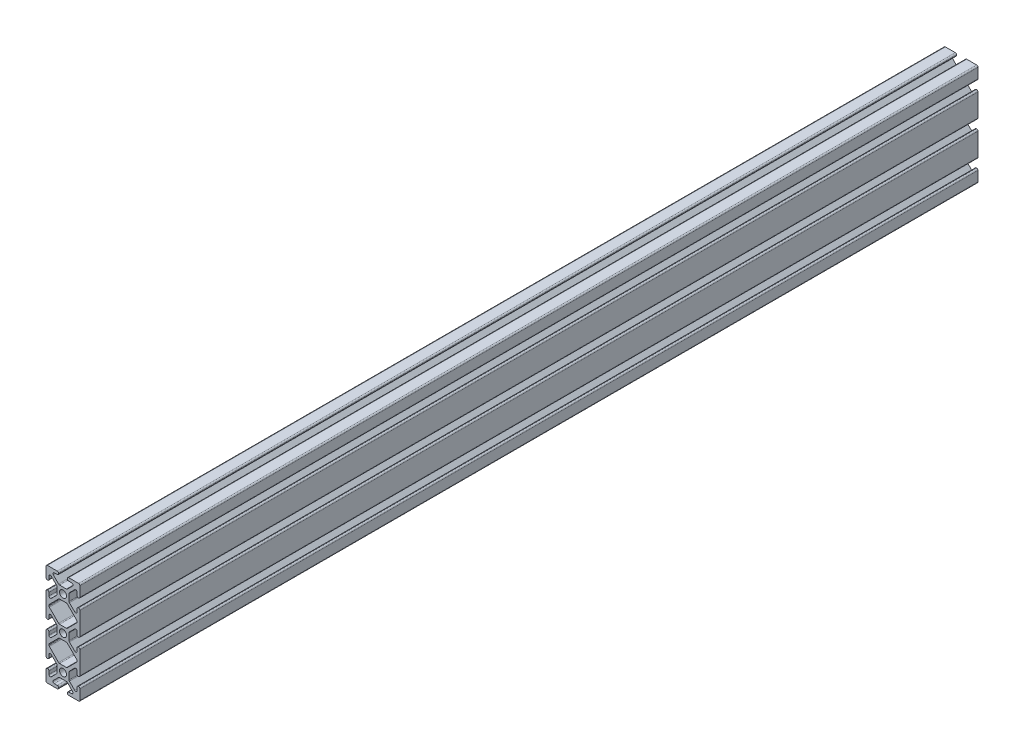
SolidWorks part; units mm, degrees
ref_plane "Front Plane" through (0, 0, 0) normal (0, 0, 1) x (1, 0, 0)
ref_plane "Top Plane" through (0, 0, 0) normal (0, 1, 0) x (1, 0, 0)
ref_plane "Right Plane" through (0, 0, 0) normal (1, 0, 0) x (0, 0, -1)
sketch "Sketch1" plane through (0, 0, 0) normal (0, 0, 1) x (1, 0, 0)
  line L0 (-12.7, 38.1) -> (-12.7, 12.7) construction
  line L1 (-12.7, -38.1) -> (12.7, -38.1) construction
  line L2 (-12.7, 12.7) -> (-12.7, -12.7) construction
  line L3 (-12.7, 38.1) -> (12.7, 38.1) construction
  line L4 (-12.7, -12.7) -> (-12.7, -38.1) construction
  line L5 (-12.7, -38.1) -> (12.7, 38.1) construction
  line L6 (-12.7, 38.1) -> (12.7, -38.1) construction
  line L7 (12.7, 38.1) -> (12.7, 12.7) construction
  line L8 (12.7, 12.7) -> (12.7, -12.7) construction
  line L9 (12.7, -12.7) -> (12.7, -38.1) construction
  line L10 (-12.7, 12.7) -> (12.7, 12.7) construction
  line L11 (-12.7, -12.7) -> (12.7, -12.7) construction
  line L12 (12.7, -12.7) -> (-12.7, -38.1) construction
  line L13 (12.7, -38.1) -> (-12.7, -12.7) construction
  line L14 (0, 38.1) -> (0, -38.1) construction
  line L15 (12.7, 12.7) -> (-12.7, 38.1) construction
  line L16 (12.7, 38.1) -> (-12.7, 12.7) construction
  line L17 (-12.7, 37.084) -> (-12.7, 29.6672)
  line L18 (-11.684, 28.6512) -> (-11.5062, 28.6512)
  line L19 (-10.4902, 29.6672) -> (-10.4902, 31.8748)
  line L20 (-8.7558, 32.5932) -> (-4.8188, 28.6562)
  line L21 (-4.5212, 27.9378) -> (-4.5212, 22.8622)
  line L22 (-4.8188, 22.1438) -> (-8.7558, 18.2068)
  line L23 (-10.4902, 18.9252) -> (-10.4902, 21.1328)
  line L24 (-11.5062, 22.1488) -> (-11.684, 22.1488)
  line L25 (-12.7, 21.1328) -> (-12.7, 4.2672)
  line L26 (-12.7, 0) -> (12.7, 0) construction
  line L27 (-12.7, -25.4) -> (12.7, -25.4) construction
  line L28 (-12.7, 25.4) -> (12.7, 25.4) construction
  line L29 (4.2672, 38.1) -> (11.684, 38.1)
  line L30 (3.2512, 36.9062) -> (3.2512, 37.084)
  line L31 (6.4748, 35.8902) -> (4.2672, 35.8902)
  line L32 (3.2562, 30.2188) -> (7.1932, 34.1558)
  line L33 (-2.5378, 29.9212) -> (2.5378, 29.9212)
  line L34 (-7.1932, 34.1558) -> (-3.2562, 30.2188)
  line L35 (-4.2672, 35.8902) -> (-6.4748, 35.8902)
  line L36 (-3.2512, 37.084) -> (-3.2512, 36.9062)
  line L37 (-11.684, 38.1) -> (-4.2672, 38.1)
  line L38 (4.5212, 2.5378) -> (4.5212, -2.5378)
  line L39 (11.5062, 22.1488) -> (11.684, 22.1488)
  line L40 (10.4902, 18.9252) -> (10.4902, 21.1328)
  line L41 (4.8188, 22.1438) -> (8.7558, 18.2068)
  line L42 (4.5212, 27.9378) -> (4.5212, 22.8622)
  line L43 (8.7558, 32.5932) -> (4.8188, 28.6562)
  line L44 (10.4902, 29.6672) -> (10.4902, 31.8748)
  line L45 (11.684, 28.6512) -> (11.5062, 28.6512)
  line L46 (12.7, 37.084) -> (12.7, 29.6672)
  line L47 (-10.4902, 12.4736) -> (-10.4902, 12.9264)
  line L48 (-10.1926, 13.6448) -> (-3.2562, 20.5812)
  line L49 (-2.5378, 20.8788) -> (2.5378, 20.8788)
  line L50 (10.4902, 12.4736) -> (10.4902, 12.9264)
  line L51 (10.1926, 13.6448) -> (3.2562, 20.5812)
  line L52 (10.1926, 11.7552) -> (3.2562, 4.8188)
  line L53 (-2.5378, 4.5212) -> (2.5378, 4.5212)
  line L54 (-10.1926, 11.7552) -> (-3.2562, 4.8188)
  line L55 (-2.5378, -4.5212) -> (2.5378, -4.5212)
  line L56 (-10.1926, -11.7552) -> (-3.2562, -4.8188)
  line L57 (10.1926, -11.7552) -> (3.2562, -4.8188)
  line L58 (10.4902, -12.4736) -> (10.4902, -12.9264)
  line L59 (10.1926, -13.6448) -> (3.2562, -20.5812)
  line L60 (-2.5378, -20.8788) -> (2.5378, -20.8788)
  line L61 (-10.1926, -13.6448) -> (-3.2562, -20.5812)
  line L62 (-10.4902, -12.4736) -> (-10.4902, -12.9264)
  line L63 (4.8188, -3.2562) -> (8.7558, -7.1932)
  line L64 (11.5062, -22.1488) -> (11.684, -22.1488)
  line L65 (10.4902, -18.9252) -> (10.4902, -21.1328)
  line L66 (4.8188, -22.1438) -> (8.7558, -18.2068)
  line L67 (4.5212, -27.9378) -> (4.5212, -22.8622)
  line L68 (8.7558, -32.5932) -> (4.8188, -28.6562)
  line L69 (10.4902, -29.6672) -> (10.4902, -31.8748)
  line L70 (11.684, -28.6512) -> (11.5062, -28.6512)
  line L71 (12.7, -37.084) -> (12.7, -29.6672)
  line L72 (3.2512, -36.9062) -> (3.2512, -37.084)
  line L73 (6.4748, -35.8902) -> (4.2672, -35.8902)
  line L74 (3.2562, -30.2188) -> (7.1932, -34.1558)
  line L75 (-2.5378, -29.9212) -> (2.5378, -29.9212)
  line L76 (-7.1932, -34.1558) -> (-3.2562, -30.2188)
  line L77 (-4.2672, -35.8902) -> (-6.4748, -35.8902)
  line L78 (-3.2512, -37.084) -> (-3.2512, -36.9062)
  line L79 (-11.684, -38.1) -> (-4.2672, -38.1)
  line L80 (4.2672, -38.1) -> (11.684, -38.1)
  line L81 (4.8188, 3.2562) -> (8.7558, 7.1932)
  line L82 (-11.5062, -22.1488) -> (-11.684, -22.1488)
  line L83 (-10.4902, -18.9252) -> (-10.4902, -21.1328)
  line L84 (-4.8188, -22.1438) -> (-8.7558, -18.2068)
  line L85 (-4.5212, -27.9378) -> (-4.5212, -22.8622)
  line L86 (-8.7558, -32.5932) -> (-4.8188, -28.6562)
  line L87 (-10.4902, -29.6672) -> (-10.4902, -31.8748)
  line L88 (-11.684, -28.6512) -> (-11.5062, -28.6512)
  line L89 (-12.7, -37.084) -> (-12.7, -29.6672)
  line L90 (-4.8188, 3.2562) -> (-8.7558, 7.1932)
  line L91 (-10.4902, 6.4748) -> (-10.4902, 4.2672)
  line L92 (-11.5062, 3.2512) -> (-11.684, 3.2512)
  line L93 (-4.5212, 2.5378) -> (-4.5212, -2.5378)
  line L94 (-12.7, -21.1328) -> (-12.7, -4.2672)
  line L95 (-4.8188, -3.2562) -> (-8.7558, -7.1932)
  line L96 (-10.4902, -6.4748) -> (-10.4902, -4.2672)
  line L97 (-11.5062, -3.2512) -> (-11.684, -3.2512)
  line L98 (10.4902, -6.4748) -> (10.4902, -4.2672)
  line L99 (10.4902, 6.4748) -> (10.4902, 4.2672)
  line L100 (11.5062, 3.2512) -> (11.684, 3.2512)
  line L101 (11.5062, -3.2512) -> (11.684, -3.2512)
  line L102 (12.7, -21.1328) -> (12.7, -4.2672)
  line L103 (12.7, 21.1328) -> (12.7, 4.2672)
  circle A0 centre (0, 25.4) radius 2.6035
  circle A1 centre (0, 0) radius 2.6035
  circle A2 centre (0, -25.4) radius 2.6035
  arc A3 (-12.7, 21.1328) -> (-11.684, 22.1488) centre (-11.684, 21.1328) cw
  arc A4 (-11.5062, 22.1488) -> (-10.4902, 21.1328) centre (-11.5062, 21.1328) cw
  arc A5 (-10.4902, 18.9252) -> (-8.7558, 18.2068) centre (-9.4742, 18.9252) ccw
  arc A6 (-4.8188, 22.1438) -> (-4.5212, 22.8622) centre (-5.5372, 22.8622) ccw
  arc A7 (-4.5212, 27.9378) -> (-4.8188, 28.6562) centre (-5.5372, 27.9378) ccw
  arc A8 (-8.7558, 32.5932) -> (-10.4902, 31.8748) centre (-9.4742, 31.8748) ccw
  arc A9 (-10.4902, 29.6672) -> (-11.5062, 28.6512) centre (-11.5062, 29.6672) cw
  arc A10 (-11.684, 28.6512) -> (-12.7, 29.6672) centre (-11.684, 29.6672) cw
  arc A11 (4.2672, 38.1) -> (3.2512, 37.084) centre (4.2672, 37.084) ccw
  arc A12 (3.2512, 36.9062) -> (4.2672, 35.8902) centre (4.2672, 36.9062) ccw
  arc A13 (6.4748, 35.8902) -> (7.1932, 34.1558) centre (6.4748, 34.8742) cw
  arc A14 (3.2562, 30.2188) -> (2.5378, 29.9212) centre (2.5378, 30.9372) cw
  arc A15 (-2.5378, 29.9212) -> (-3.2562, 30.2188) centre (-2.5378, 30.9372) cw
  arc A16 (-7.1932, 34.1558) -> (-6.4748, 35.8902) centre (-6.4748, 34.8742) cw
  arc A17 (-4.2672, 35.8902) -> (-3.2512, 36.9062) centre (-4.2672, 36.9062) ccw
  arc A18 (-3.2512, 37.084) -> (-4.2672, 38.1) centre (-4.2672, 37.084) ccw
  arc A19 (12.7, 21.1328) -> (11.684, 22.1488) centre (11.684, 21.1328) ccw
  arc A20 (11.5062, 22.1488) -> (10.4902, 21.1328) centre (11.5062, 21.1328) ccw
  arc A21 (10.4902, 18.9252) -> (8.7558, 18.2068) centre (9.4742, 18.9252) cw
  arc A22 (4.8188, 22.1438) -> (4.5212, 22.8622) centre (5.5372, 22.8622) cw
  arc A23 (4.5212, 27.9378) -> (4.8188, 28.6562) centre (5.5372, 27.9378) cw
  arc A24 (8.7558, 32.5932) -> (10.4902, 31.8748) centre (9.4742, 31.8748) cw
  arc A25 (10.4902, 29.6672) -> (11.5062, 28.6512) centre (11.5062, 29.6672) ccw
  arc A26 (11.684, 28.6512) -> (12.7, 29.6672) centre (11.684, 29.6672) ccw
  arc A27 (12.7, 37.084) -> (11.684, 38.1) centre (11.684, 37.084) ccw
  arc A28 (-11.684, 38.1) -> (-12.7, 37.084) centre (-11.684, 37.084) ccw
  arc A29 (-10.1926, 13.6448) -> (-10.4902, 12.9264) centre (-9.4742, 12.9264) ccw
  arc A30 (-2.5378, 20.8788) -> (-3.2562, 20.5812) centre (-2.5378, 19.8628) ccw
  arc A31 (10.1926, 13.6448) -> (10.4902, 12.9264) centre (9.4742, 12.9264) cw
  arc A32 (2.5378, 20.8788) -> (3.2562, 20.5812) centre (2.5378, 19.8628) cw
  arc A33 (10.1926, 11.7552) -> (10.4902, 12.4736) centre (9.4742, 12.4736) ccw
  arc A34 (2.5378, 4.5212) -> (3.2562, 4.8188) centre (2.5378, 5.5372) ccw
  arc A35 (-2.5378, 4.5212) -> (-3.2562, 4.8188) centre (-2.5378, 5.5372) cw
  arc A36 (-10.1926, 11.7552) -> (-10.4902, 12.4736) centre (-9.4742, 12.4736) cw
  arc A37 (2.5378, -4.5212) -> (3.2562, -4.8188) centre (2.5378, -5.5372) cw
  arc A38 (-2.5378, -4.5212) -> (-3.2562, -4.8188) centre (-2.5378, -5.5372) ccw
  arc A39 (10.1926, -11.7552) -> (10.4902, -12.4736) centre (9.4742, -12.4736) cw
  arc A40 (10.1926, -13.6448) -> (10.4902, -12.9264) centre (9.4742, -12.9264) ccw
  arc A41 (2.5378, -20.8788) -> (3.2562, -20.5812) centre (2.5378, -19.8628) ccw
  arc A42 (-2.5378, -20.8788) -> (-3.2562, -20.5812) centre (-2.5378, -19.8628) cw
  arc A43 (-10.1926, -13.6448) -> (-10.4902, -12.9264) centre (-9.4742, -12.9264) cw
  arc A44 (-10.1926, -11.7552) -> (-10.4902, -12.4736) centre (-9.4742, -12.4736) ccw
  arc A45 (12.7, -21.1328) -> (11.684, -22.1488) centre (11.684, -21.1328) cw
  arc A46 (11.5062, -22.1488) -> (10.4902, -21.1328) centre (11.5062, -21.1328) cw
  arc A47 (10.4902, -18.9252) -> (8.7558, -18.2068) centre (9.4742, -18.9252) ccw
  arc A48 (4.8188, -22.1438) -> (4.5212, -22.8622) centre (5.5372, -22.8622) ccw
  arc A49 (4.5212, -27.9378) -> (4.8188, -28.6562) centre (5.5372, -27.9378) ccw
  arc A50 (8.7558, -32.5932) -> (10.4902, -31.8748) centre (9.4742, -31.8748) ccw
  arc A51 (10.4902, -29.6672) -> (11.5062, -28.6512) centre (11.5062, -29.6672) cw
  arc A52 (11.684, -28.6512) -> (12.7, -29.6672) centre (11.684, -29.6672) cw
  arc A53 (4.2672, -38.1) -> (3.2512, -37.084) centre (4.2672, -37.084) cw
  arc A54 (3.2512, -36.9062) -> (4.2672, -35.8902) centre (4.2672, -36.9062) cw
  arc A55 (6.4748, -35.8902) -> (7.1932, -34.1558) centre (6.4748, -34.8742) ccw
  arc A56 (3.2562, -30.2188) -> (2.5378, -29.9212) centre (2.5378, -30.9372) ccw
  arc A57 (-2.5378, -29.9212) -> (-3.2562, -30.2188) centre (-2.5378, -30.9372) ccw
  arc A58 (-7.1932, -34.1558) -> (-6.4748, -35.8902) centre (-6.4748, -34.8742) ccw
  arc A59 (-4.2672, -35.8902) -> (-3.2512, -36.9062) centre (-4.2672, -36.9062) cw
  arc A60 (-3.2512, -37.084) -> (-4.2672, -38.1) centre (-4.2672, -37.084) cw
  arc A61 (12.7, -37.084) -> (11.684, -38.1) centre (11.684, -37.084) cw
  arc A62 (-12.7, -21.1328) -> (-11.684, -22.1488) centre (-11.684, -21.1328) ccw
  arc A63 (-11.5062, -22.1488) -> (-10.4902, -21.1328) centre (-11.5062, -21.1328) ccw
  arc A64 (-10.4902, -18.9252) -> (-8.7558, -18.2068) centre (-9.4742, -18.9252) cw
  arc A65 (-4.8188, -22.1438) -> (-4.5212, -22.8622) centre (-5.5372, -22.8622) cw
  arc A66 (-4.5212, -27.9378) -> (-4.8188, -28.6562) centre (-5.5372, -27.9378) cw
  arc A67 (-8.7558, -32.5932) -> (-10.4902, -31.8748) centre (-9.4742, -31.8748) cw
  arc A68 (-10.4902, -29.6672) -> (-11.5062, -28.6512) centre (-11.5062, -29.6672) ccw
  arc A69 (-11.684, -28.6512) -> (-12.7, -29.6672) centre (-11.684, -29.6672) ccw
  arc A70 (-11.684, -38.1) -> (-12.7, -37.084) centre (-11.684, -37.084) cw
  arc A71 (-4.8188, 3.2562) -> (-4.5212, 2.5378) centre (-5.5372, 2.5378) cw
  arc A72 (-10.4902, 6.4748) -> (-8.7558, 7.1932) centre (-9.4742, 6.4748) cw
  arc A73 (-11.5062, 3.2512) -> (-10.4902, 4.2672) centre (-11.5062, 4.2672) ccw
  arc A74 (-12.7, 4.2672) -> (-11.684, 3.2512) centre (-11.684, 4.2672) ccw
  arc A75 (-4.8188, -3.2562) -> (-4.5212, -2.5378) centre (-5.5372, -2.5378) ccw
  arc A76 (-10.4902, -6.4748) -> (-8.7558, -7.1932) centre (-9.4742, -6.4748) ccw
  arc A77 (-11.5062, -3.2512) -> (-10.4902, -4.2672) centre (-11.5062, -4.2672) cw
  arc A78 (-12.7, -4.2672) -> (-11.684, -3.2512) centre (-11.684, -4.2672) cw
  arc A79 (4.8188, 3.2562) -> (4.5212, 2.5378) centre (5.5372, 2.5378) ccw
  arc A80 (4.8188, -3.2562) -> (4.5212, -2.5378) centre (5.5372, -2.5378) cw
  arc A81 (10.4902, 6.4748) -> (8.7558, 7.1932) centre (9.4742, 6.4748) ccw
  arc A82 (10.4902, -6.4748) -> (8.7558, -7.1932) centre (9.4742, -6.4748) cw
  arc A83 (11.5062, -3.2512) -> (10.4902, -4.2672) centre (11.5062, -4.2672) ccw
  arc A84 (11.5062, 3.2512) -> (10.4902, 4.2672) centre (11.5062, 4.2672) cw
  arc A85 (12.7, -4.2672) -> (11.684, -3.2512) centre (11.684, -4.2672) ccw
  arc A86 (12.7, 4.2672) -> (11.684, 3.2512) centre (11.684, 4.2672) cw
  point P0 (0, 0)
  point P26 (-12.7, 22.1488)
  point P41 (-12.7, 28.6512)
  point P107 (-6.7244, 17.113)
  point P120 (0, 20.8788)
  point P121 (10.4902, 12.7)
  point P132 (-10.4902, 12.7)
  point P249 (-4.5212, 0)
  dimension "D2" = 5.207
  dimension "D8" = 1.016
  dimension "D9" = 3.2512
  dimension "D10" = 1.1049
  dimension "D1" = 25.4
  dimension "D3" = 2.2098
  dimension "D4" = 6.5024
  dimension "D5" = 4.5212
  dimension "D6" = 1.1049
  dimension "D7" = 1.1049
  dimension "D11" = 4.5212
extrude "Main Extrusion" add sketch "Sketch1" along normal mid plane 671.3474
sketch "Sketch2" plane through (0, 0, 335.6737) normal (0, 0, 1) x (1, 0, 0)
  line L0 (-4.2672, 38.1) -> (-11.684, 38.1) construction
  line L1 (-12.7, -38.1) -> (12.7, -38.1) construction
  line L2 (-12.7, 38.1) -> (-12.7, 12.7) construction
  line L3 (-12.7, 38.1) -> (12.7, 38.1) construction
  line L4 (-12.7, 21.1328) -> (-12.7, 4.2672) construction
  line L5 (-12.7, -38.1) -> (12.7, 38.1) construction
  line L6 (-12.7, 38.1) -> (12.7, -38.1) construction
  line L7 (-12.7, 12.7) -> (-12.7, -12.7) construction
  line L8 (0, 38.1) -> (0, -38.1) construction
  line L9 (-12.7, -4.2672) -> (-12.7, -21.1328) construction
  line L10 (-12.7, -12.7) -> (-12.7, -38.1) construction
  line L11 (12.7, 38.1) -> (12.7, 12.7) construction
  line L12 (12.7, 4.2672) -> (12.7, 21.1328) construction
  line L13 (12.7, 12.7) -> (12.7, -12.7) construction
  line L14 (12.7, -21.1328) -> (12.7, -4.2672) construction
  line L15 (12.7, -12.7) -> (12.7, -38.1) construction
  line L16 (-12.7, 25.4) -> (12.7, 25.4) construction
  line L17 (-12.7, 0) -> (12.7, 0) construction
  line L18 (-12.7, -25.4) -> (12.7, -25.4) construction
  line L19 (-12.7, 12.7) -> (12.7, 12.7) construction
  line L20 (-12.7, -12.7) -> (12.7, -12.7) construction
  line L21 (-3.2512, 36.9062) -> (-3.2512, 37.084) construction
  line L22 (-10.4902, 38.1) -> (-9.4742, 38.1)
  line L23 (-6.477, 38.1) -> (-5.461, 38.1)
  line L24 (-12.7, 38.1) -> (12.7, 12.7) construction
  line L25 (12.7, 12.7) -> (-12.7, -12.7) construction
  line L26 (-12.7, -12.7) -> (12.7, -38.1) construction
  line L27 (-12.7, -38.1) -> (12.7, -12.7) construction
  line L28 (12.7, -12.7) -> (-12.7, 12.7) construction
  line L29 (-12.7, 12.7) -> (12.7, 38.1) construction
  line L30 (6.477, 38.1) -> (5.461, 38.1)
  line L31 (10.4902, 38.1) -> (9.4742, 38.1)
  line L32 (-12.7, 14.9098) -> (-12.7, 15.9258)
  line L33 (-12.7, 18.923) -> (-12.7, 19.939)
  line L34 (-12.7, 31.877) -> (-12.7, 30.861)
  line L35 (-12.7, 35.8902) -> (-12.7, 34.8742)
  line L36 (12.7, 35.8902) -> (12.7, 34.8742)
  line L37 (12.7, 31.877) -> (12.7, 30.861)
  line L38 (12.7, 18.923) -> (12.7, 19.939)
  line L39 (12.7, 14.9098) -> (12.7, 15.9258)
  line L40 (12.7, 10.4902) -> (12.7, 9.4742)
  line L41 (12.7, 6.477) -> (12.7, 5.461)
  line L42 (-12.7, 10.4902) -> (-12.7, 9.4742)
  line L43 (-12.7, 6.477) -> (-12.7, 5.461)
  line L44 (12.7, -6.477) -> (12.7, -5.461)
  line L45 (12.7, -10.4902) -> (12.7, -9.4742)
  line L46 (12.7, -14.9098) -> (12.7, -15.9258)
  line L47 (12.7, -18.923) -> (12.7, -19.939)
  line L48 (12.7, -31.877) -> (12.7, -30.861)
  line L49 (12.7, -35.8902) -> (12.7, -34.8742)
  line L50 (10.4902, -38.1) -> (9.4742, -38.1)
  line L51 (6.477, -38.1) -> (5.461, -38.1)
  line L52 (-6.477, -38.1) -> (-5.461, -38.1)
  line L53 (-10.4902, -38.1) -> (-9.4742, -38.1)
  line L54 (-12.7, -35.8902) -> (-12.7, -34.8742)
  line L55 (-12.7, -31.877) -> (-12.7, -30.861)
  line L56 (-12.7, -18.923) -> (-12.7, -19.939)
  line L57 (-12.7, -14.9098) -> (-12.7, -15.9258)
  line L58 (-12.7, -10.4902) -> (-12.7, -9.4742)
  line L59 (-12.7, -6.477) -> (-12.7, -5.461)
  arc A0 (-10.4902, 38.1) -> (-9.4742, 38.1) centre (-9.9822, 38.1) ccw
  arc A1 (-6.477, 38.1) -> (-5.461, 38.1) centre (-5.969, 38.1) ccw
  arc A2 (6.477, 38.1) -> (5.461, 38.1) centre (5.969, 38.1) cw
  arc A3 (10.4902, 38.1) -> (9.4742, 38.1) centre (9.9822, 38.1) cw
  arc A4 (-12.7, 14.9098) -> (-12.7, 15.9258) centre (-12.7, 15.4178) ccw
  arc A5 (-12.7, 18.923) -> (-12.7, 19.939) centre (-12.7, 19.431) ccw
  arc A6 (-12.7, 31.877) -> (-12.7, 30.861) centre (-12.7, 31.369) cw
  arc A7 (-12.7, 35.8902) -> (-12.7, 34.8742) centre (-12.7, 35.3822) cw
  arc A8 (12.7, 35.8902) -> (12.7, 34.8742) centre (12.7, 35.3822) ccw
  arc A9 (12.7, 31.877) -> (12.7, 30.861) centre (12.7, 31.369) ccw
  arc A10 (12.7, 18.923) -> (12.7, 19.939) centre (12.7, 19.431) cw
  arc A11 (12.7, 14.9098) -> (12.7, 15.9258) centre (12.7, 15.4178) cw
  arc A12 (12.7, 10.4902) -> (12.7, 9.4742) centre (12.7, 9.9822) ccw
  arc A13 (12.7, 6.477) -> (12.7, 5.461) centre (12.7, 5.969) ccw
  arc A14 (-12.7, 10.4902) -> (-12.7, 9.4742) centre (-12.7, 9.9822) cw
  arc A15 (-12.7, 6.477) -> (-12.7, 5.461) centre (-12.7, 5.969) cw
  arc A16 (12.7, -6.477) -> (12.7, -5.461) centre (12.7, -5.969) cw
  arc A17 (12.7, -10.4902) -> (12.7, -9.4742) centre (12.7, -9.9822) cw
  arc A18 (12.7, -14.9098) -> (12.7, -15.9258) centre (12.7, -15.4178) ccw
  arc A19 (12.7, -18.923) -> (12.7, -19.939) centre (12.7, -19.431) ccw
  arc A20 (12.7, -31.877) -> (12.7, -30.861) centre (12.7, -31.369) cw
  arc A21 (12.7, -35.8902) -> (12.7, -34.8742) centre (12.7, -35.3822) cw
  arc A22 (10.4902, -38.1) -> (9.4742, -38.1) centre (9.9822, -38.1) ccw
  arc A23 (6.477, -38.1) -> (5.461, -38.1) centre (5.969, -38.1) ccw
  arc A24 (-6.477, -38.1) -> (-5.461, -38.1) centre (-5.969, -38.1) cw
  arc A25 (-10.4902, -38.1) -> (-9.4742, -38.1) centre (-9.9822, -38.1) cw
  arc A26 (-12.7, -35.8902) -> (-12.7, -34.8742) centre (-12.7, -35.3822) ccw
  arc A27 (-12.7, -31.877) -> (-12.7, -30.861) centre (-12.7, -31.369) ccw
  arc A28 (-12.7, -18.923) -> (-12.7, -19.939) centre (-12.7, -19.431) cw
  arc A29 (-12.7, -14.9098) -> (-12.7, -15.9258) centre (-12.7, -15.4178) cw
  arc A30 (-12.7, -10.4902) -> (-12.7, -9.4742) centre (-12.7, -9.9822) ccw
  arc A31 (-12.7, -6.477) -> (-12.7, -5.461) centre (-12.7, -5.969) ccw
  point P0 (0, 0)
  dimension "D1" = 0.508
  dimension "D2" = 2.2098
  dimension "D3" = 2.2098
